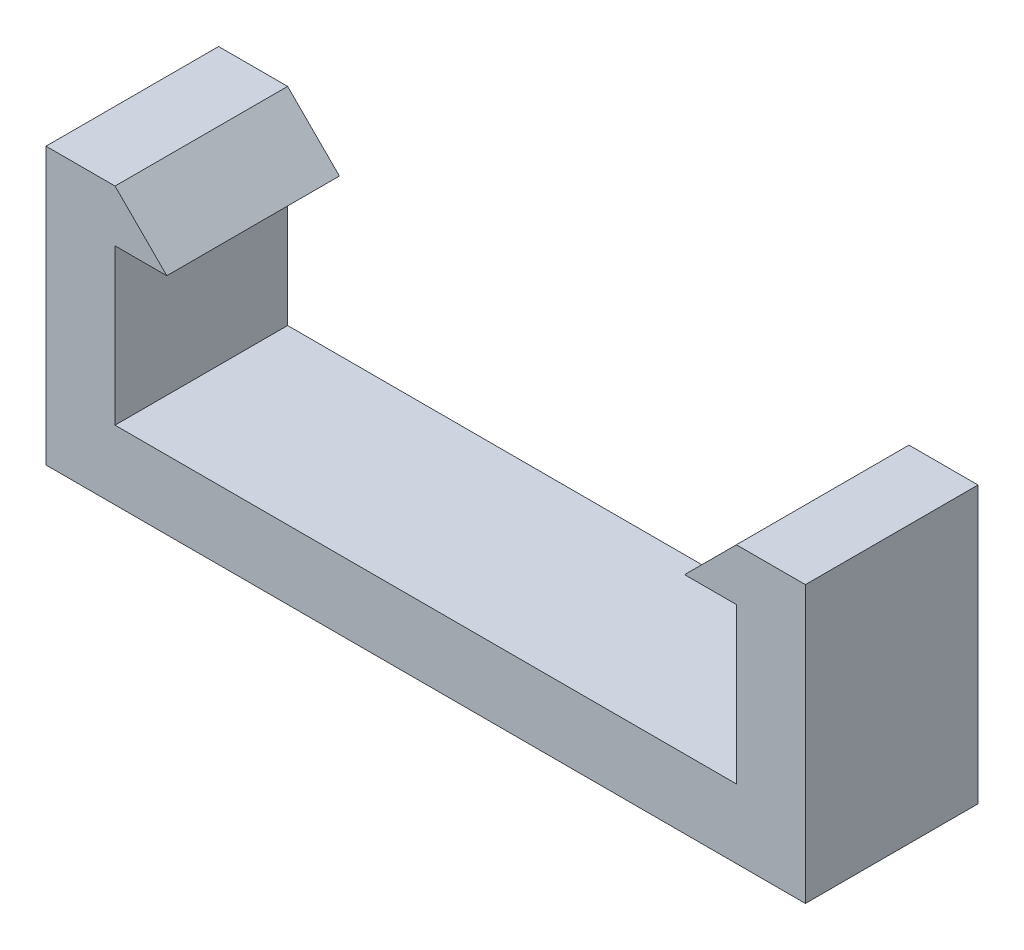
SolidWorks part; units mm, degrees
ref_plane "Front Plane" through (0, 0, 0) normal (0, 0, 1) x (1, 0, 0)
ref_plane "Top Plane" through (0, 0, 0) normal (0, 1, 0) x (1, 0, 0)
ref_plane "Right Plane" through (0, 0, 0) normal (1, 0, 0) x (0, 0, -1)
sketch "Sketch1" plane through (0, 0, 0) normal (0, 0, 1) x (1, 0, 0)
  line L0 (0, 0) -> (0, -8)
  line L1 (0, -8) -> (22, -8)
  line L2 (22, -8) -> (22, 0)
  line L3 (22, 0) -> (20, 0)
  line L4 (20, -1.5) -> (20, -6)
  line L5 (20, -6) -> (2, -6)
  line L6 (2, -6) -> (2, -1.5)
  line L7 (2, 0) -> (0, 0)
  line L8 (2, -1.5) -> (3.5, -1.5)
  line L9 (3.5, -1.5) -> (2, 0)
  line L10 (20, -1.5) -> (18.5, -1.5)
  line L11 (18.5, -1.5) -> (20, 0)
  point P13 (0, 0)
  dimension "D1" = 18
  dimension "D2" = 2
  dimension "D3" = 2
  dimension "D4" = 1.5
  dimension "D5" = 4.5
  dimension "D6" = 8
  dimension "D7" = 2
extrude "Boss-Extrude1" add sketch "Sketch1" along normal blind 5
